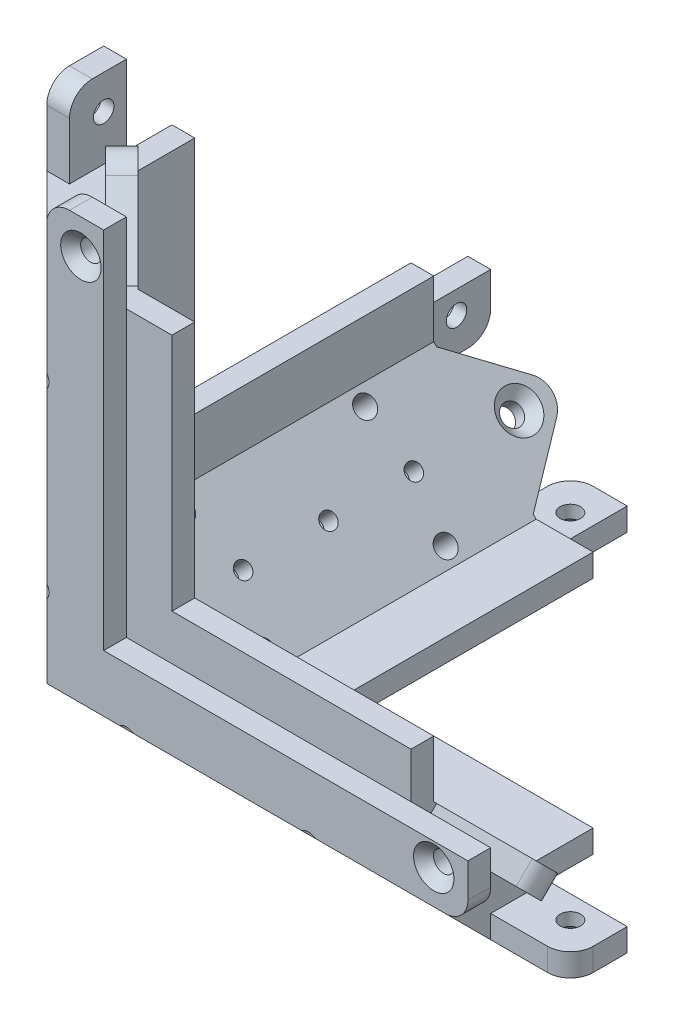
SolidWorks part; units mm, degrees
ref_plane "Front Plane" through (0, 0, 0) normal (0, 0, 1) x (1, 0, 0)
ref_plane "Top Plane" through (0, 0, 0) normal (0, 1, 0) x (1, 0, 0)
ref_plane "Right Plane" through (0, 0, 0) normal (1, 0, 0) x (0, 0, -1)
sketch "Sketch1" plane through (0, 0, 0) normal (1, 0, 0) x (0, 0, -1)
  line L0 (0, 36) -> (0, 0)
  line L1 (0, 0) -> (36, 0)
  line L2 (36, 0) -> (36, 8)
  line L3 (36, 8) -> (8, 8)
  line L4 (8, 8) -> (8, 36)
  line L5 (8, 36) -> (0, 36)
  dimension "D1" = 8
  dimension "D2" = 8
  dimension "D3" = 36
  dimension "D4" = 36
extrude "Boss-Extrude1" add sketch "Sketch1" along normal blind 78
sketch "Sketch2" plane through (0, 0, -8) normal (0, 0, -1) x (-1, 0, 0)
  line L0 (0, 36) -> (-8, 36)
  line L1 (-78, 36) -> (0, 36) construction
  line L2 (-8, 36) -> (-8, 8)
  line L3 (-78, 8) -> (0, 8) construction
  line L4 (-8, 8) -> (-36, 8)
  line L5 (-36, 8) -> (-36, 0)
  line L6 (-78, 0) -> (0, 0) construction
  line L7 (-36, 0) -> (0, 0)
  line L8 (0, 0) -> (0, 36)
  dimension "D1" = 8
  dimension "D2" = 36
extrude "Boss-Extrude2" add sketch "Sketch2" along normal blind 70
sketch "Sketch3" plane through (0, 8, 0) normal (0, 1, 0) x (1, 0, 0)
  line L0 (0, 0) -> (0, 36)
  line L1 (0, 78) -> (0, 0) construction
  line L2 (0, 36) -> (8, 36)
  line L3 (8, 78) -> (8, 8) construction
  line L4 (8, 36) -> (8, 8)
  line L5 (78, 8) -> (8, 8) construction
  line L6 (8, 8) -> (36, 8)
  line L7 (78, 8) -> (8, 8) construction
  line L8 (36, 8) -> (36, 0)
  line L9 (78, 0) -> (0, 0) construction
  line L10 (36, 0) -> (0, 0)
  dimension "D1" = 36
  dimension "D2" = 36
extrude "Boss-Extrude3" add sketch "Sketch3" along normal blind 70
chamfer "Chamfer1" distance 18 angle 45 3 edges at (43, 8, -8) (8, 8, -43) (8, 43, -8)
chamfer "Chamfer2" distance 18 angle 45 3 edges at (0, 0, -39) (39, 0, 0) (0, 39, 0)
sketch "Sketch4" plane through (0, 0, 0) normal (0, -1, 0) x (-1, 0, 0)
  line L0 (-36, 78) -> (-18, 78) construction
  line L1 (-28, 28) -> (-128.9953, 28)
  line L2 (-28, 28) -> (-28, 78)
  line L3 (-28, 78) -> (-128.9953, 78)
  line L4 (-128.9953, 28) -> (-128.9953, 78)
  dimension "D1" = 8
  dimension "D2" = 8
extrude "Cut-Extrude1" cut sketch "Sketch4" against normal blind 4
sketch "Sketch5" plane through (0, 0, 0) normal (0, 0, 1) x (1, 0, 0)
  line L0 (18, 78) -> (36, 78) construction
  line L1 (28, 78) -> (78, 78)
  line L2 (28, 78) -> (28, 28)
  line L3 (28, 28) -> (78, 28)
  line L4 (78, 78) -> (78, 28)
  line L6 (78, 36) -> (78, 18) construction
  dimension "D1" = 8
  dimension "D2" = 8
extrude "Cut-Extrude2" cut sketch "Sketch5" against normal blind 4
sketch "Sketch6" plane through (0, 0, 0) normal (-1, 0, 0) x (0, 0, 1)
  line L1 (-28, 78) -> (-78, 78)
  line L2 (-28, 78) -> (-28, 28)
  line L3 (-28, 28) -> (-78, 28)
  line L4 (-78, 78) -> (-78, 28)
  line L7 (-36, 78) -> (-18, 78) construction
  line L8 (-78, 18) -> (-78, 36) construction
  dimension "D1" = 8
  dimension "D2" = 8
extrude "Cut-Extrude3" cut sketch "Sketch6" against normal blind 4
sketch "Sketch7" plane through (17, 17, 0) normal (0.7071, 0.7071, 0) x (0, 0, -1)
  line L0 (78, 12.7279) -> (78, -12.7279) construction
  circle A0 centre (65.5, 0) radius 1.4
  circle A7 centre (50.5, 0) radius 1.4
  circle A8 centre (35.5, 0) radius 1.4
  dimension "D1" = 2.8
  dimension "D2" = 12.5
  dimension "D3" = 3
sketch "Sketch8" plane through (17, 0, -17) normal (0.7071, 0, -0.7071) x (-0.7071, 0, -0.7071)
  line L1 (-12.7279, 78) -> (12.7279, 78) construction
  line L2 (0, 65.5) -> (0, 50.5) construction
  circle A7 centre (0, 65.5) radius 1.4
  circle A8 centre (0, 50.5) radius 1.4
  circle A9 centre (0, 35.5) radius 1.4
  dimension "D1" = 12.5
  dimension "D4" = 2.8
  dimension "D2" = 15
  dimension "D3" = 3
extrude "Cut-Extrude7" cut sketch "Sketch7" against normal blind 3.5
extrude "Cut-Extrude8" cut sketch "Sketch8" against normal blind 3.5
sketch "Sketch10" plane through (0, 17, -17) normal (0, 0.7071, -0.7071) x (1, 0, 0)
  line L0 (78, 12.7279) -> (78, -12.7279) construction
  circle A0 centre (65.5, 0) radius 1.4
  circle A1 centre (50.5, 0) radius 1.4
  circle A2 centre (35.5, 0) radius 1.4
  dimension "D1" = 2.8
  dimension "D2" = 12.5
extrude "Cut-Extrude9" cut sketch "Sketch10" against normal blind 3.5
sketch "Sketch11" plane through (78, 0, 0) normal (1, 0, 0) x (0, 0, -1)
  line L5 (18, 0) -> (28, 0)
  line L6 (18, 0) -> (18, 4)
  line L7 (18, 4) -> (28, 4)
  line L8 (28, 0) -> (28, 4)
  line L9 (0, 18) -> (4, 18)
  line L10 (0, 18) -> (0, 28)
  line L11 (0, 28) -> (4, 28)
  line L12 (4, 18) -> (4, 28)
extrude "Boss-Extrude4" add sketch "Sketch11" along normal blind 14
fillet "Fillet1" radius 4 2 edges at (92, 2, -18) (92, 18, -2)
sketch "Sketch12" plane through (0, 17, -17) normal (0, 0.7071, -0.7071) x (1, 0, 0)
  line L0 (78, 12) -> (92, 0)
  line L1 (78, 12.7279) -> (78, -12.7279) construction
  line L2 (92, 0) -> (78, -12)
  line L3 (78, -9.8995) -> (78, -16.9706) construction
  line L4 (78, -12) -> (78, 12)
  dimension "D1" = 12
  dimension "D2" = 14
  dimension "D3" = 12
  dimension "D4" = 12
extrude "Boss-Extrude5" add sketch "Sketch12" against normal blind 4
fillet "Fillet2" radius 4 1 edges at (92, 15.5858, -15.5858)
sketch "Sketch13" plane through (0, 0, -78) normal (0, 0, -1) x (-1, 0, 0)
  line L5 (-28, 4) -> (-18, 4)
  line L6 (-28, 4) -> (-28, 0)
  line L7 (-28, 0) -> (-18, 0)
  line L8 (-18, 4) -> (-18, 0)
  line L9 (-4, 28) -> (0, 28)
  line L10 (-4, 28) -> (-4, 18)
  line L11 (-4, 18) -> (0, 18)
  line L12 (0, 28) -> (0, 18)
extrude "Boss-Extrude6" add sketch "Sketch13" along normal blind 14
fillet "Fillet3" radius 4 2 edges at (2, 18, -92) (18, 2, -92)
sketch "Sketch14" plane through (17, 17, 0) normal (0.7071, 0.7071, 0) x (0, 0, -1)
  line L0 (78, 12) -> (92, 0)
  line L1 (78, 12.7279) -> (78, -12.7279) construction
  line L2 (92, 0) -> (78, -12)
  line L3 (78, -12) -> (78, 12)
  dimension "D1" = 12
  dimension "D2" = 12
  dimension "D3" = 14
  dimension "D4" = 12
extrude "Boss-Extrude7" add sketch "Sketch14" against normal blind 4
fillet "Fillet4" radius 4 1 edges at (15.5858, 15.5858, -92)
sketch "Sketch15" plane through (17, 0, -17) normal (0.7071, 0, -0.7071) x (-0.7071, 0, -0.7071)
  line L0 (-12, 78) -> (0, 92)
  line L1 (-12.7279, 78) -> (12.7279, 78) construction
  line L2 (0, 92) -> (12, 78)
  line L3 (12, 78) -> (-12, 78)
  dimension "D1" = 12
  dimension "D2" = 12
  dimension "D3" = 14
  dimension "D4" = 12
extrude "Boss-Extrude8" add sketch "Sketch15" against normal blind 4
fillet "Fillet5" radius 4 1 edges at (15.5858, 92, -15.5858)
sketch "Sketch16" plane through (0, 78, 0) normal (0, 1, 0) x (1, 0, 0)
  line L1 (0, 18) -> (4, 18)
  line L2 (0, 18) -> (0, 28)
  line L3 (0, 28) -> (4, 28)
  line L4 (4, 18) -> (4, 28)
  line L5 (28, 4) -> (18, 4)
  line L6 (28, 4) -> (28, 0)
  line L7 (28, 0) -> (18, 0)
  line L8 (18, 4) -> (18, 0)
extrude "Boss-Extrude9" add sketch "Sketch16" along normal blind 14
fillet "Fillet6" radius 4 2 edges at (18, 92, -2) (2, 92, -18)
sketch "Sketch17" plane through (17, 17, 0) normal (0.7071, 0.7071, 0) x (0, 0, -1)
  circle A0 centre (84, 0) radius 1.8
  dimension "D1" = 3.6
  dimension "D2" = 6
extrude "Cut-Extrude10" cut sketch "Sketch17" against normal blind 14
sketch "Sketch18" plane through (17, 0, -17) normal (0.7071, 0, -0.7071) x (-0.7071, 0, -0.7071)
  line L0 (9.8995, 78) -> (16.9706, 78) construction
  circle A0 centre (0, 84) radius 1.8
  dimension "D1" = 3.6
  dimension "D2" = 6
extrude "Cut-Extrude11" cut sketch "Sketch18" against normal blind 14
sketch "Sketch19" plane through (0, 17, -17) normal (0, 0.7071, -0.7071) x (1, 0, 0)
  circle A0 centre (84, 0) radius 1.8
  dimension "D1" = 3.6
  dimension "D2" = 6
extrude "Cut-Extrude12" cut sketch "Sketch19" against normal blind 14
sketch "Sketch20" plane through (0, 0, 0) normal (0, -1, 0) x (-1, 0, 0)
  circle A0 centre (-86, 24) radius 1.8
  circle A1 centre (-24, 86) radius 1.8
  dimension "D1" = 3.6
  dimension "D2" = 8
  dimension "D3" = 24
  dimension "D4" = 8
  dimension "D5" = 24
extrude "Cut-Extrude13" cut sketch "Sketch20" against normal blind 14
sketch "Sketch21" plane through (0, 0, 0) normal (-1, 0, 0) x (0, 0, 1)
  circle A0 centre (-24, 86) radius 1.8
  circle A1 centre (-86, 24) radius 1.8
  dimension "D3" = 3.6
  dimension "D1" = 8
  dimension "D2" = 8
  dimension "D4" = 24
  dimension "D5" = 24
extrude "Cut-Extrude14" cut sketch "Sketch21" against normal blind 14
sketch "Sketch22" plane through (0, 0, 0) normal (0, 0, 1) x (1, 0, 0)
  circle A0 centre (24, 86) radius 1.8
  circle A1 centre (86, 24) radius 1.8
  dimension "D1" = 3.6
  dimension "D2" = 8
  dimension "D3" = 8
  dimension "D4" = 24
  dimension "D5" = 24
extrude "Cut-Extrude15" cut sketch "Sketch22" against normal blind 14
chamfer "Chamfer3" distance 1.75 angle 45 9 edges at (15.7272, 18.2728, -84) (15.7272, 84, -18.2728) (84, 18.2728, -15.7272) (86, 0, -25.8) (24, 0, -87.8) (0, 86, -22.2) (0, 24, -84.2) (25.8, 86, 0) (87.8, 24, 0)
sketch "Sketch27" plane through (17, 17, 0) normal (0.7071, 0.7071, 0) x (0, 0, -1)
  circle A0 centre (32.0226, -10) radius 1.8
  circle A1 centre (32.0226, 10) radius 1.8
  circle A2 centre (64.0226, 10) radius 1.8
  circle A3 centre (64.0226, -10) radius 1.8
  dimension "D1" = 3.6
  dimension "D2" = 32
extrude "Cut-Extrude19" cut sketch "Sketch27" against normal through all
sketch "Sketch29" plane through (9, 9, 0) normal (-0.7071, -0.7071, 0) x (0, 0, 1)
  circle A0 centre (-64.0226, 10) radius 3
  circle A1 centre (-32.0226, 10) radius 3
  circle A2 centre (-32.0226, -10) radius 3
  circle A3 centre (-64.0226, -10) radius 3
  dimension "D1" = 6
extrude "Cut-Extrude20" cut sketch "Sketch29" against normal blind 4
sketch "Sketch31" plane through (9, 0, -9) normal (-0.7071, 0, 0.7071) x (0.7071, 0, 0.7071)
  circle A0 centre (-10, 64) radius 1.8
  circle A1 centre (10, 64) radius 1.8
  circle A2 centre (10, 32) radius 1.8
  circle A3 centre (-10, 32) radius 1.8
  dimension "D1" = 3.6
  dimension "D2" = 32
  dimension "D3" = 14
  dimension "D4" = 20
  dimension "D5" = 10
extrude "Cut-Extrude21" cut sketch "Sketch31" against normal through all
sketch "Sketch32" plane through (9, 0, -9) normal (-0.7071, 0, 0.7071) x (0.7071, 0, 0.7071)
  circle A0 centre (-10, 64) radius 3
  circle A1 centre (10, 64) radius 3
  circle A2 centre (10, 32) radius 3
  circle A3 centre (-10, 32) radius 3
  dimension "D1" = 6
extrude "Cut-Extrude22" cut sketch "Sketch32" against normal blind 4
sketch "Sketch33" plane through (0, 9, -9) normal (0, -0.7071, 0.7071) x (1, 0, 0)
  circle A0 centre (64, 10) radius 1.8
  circle A1 centre (64, -10) radius 1.8
  circle A2 centre (32, 10) radius 1.8
  circle A3 centre (32, -10) radius 1.8
  dimension "D1" = 3.6
  dimension "D2" = 20
  dimension "D3" = 10
  dimension "D4" = 32
  dimension "D5" = 14
extrude "Cut-Extrude23" cut sketch "Sketch33" against normal through all
sketch "Sketch34" plane through (0, 9, -9) normal (0, -0.7071, 0.7071) x (1, 0, 0)
  circle A0 centre (32, 10) radius 3
  circle A1 centre (64, 10) radius 3
  circle A2 centre (64, -10) radius 3
  circle A3 centre (32, -10) radius 3
  dimension "D1" = 6
extrude "Cut-Extrude24" cut sketch "Sketch34" against normal blind 4
